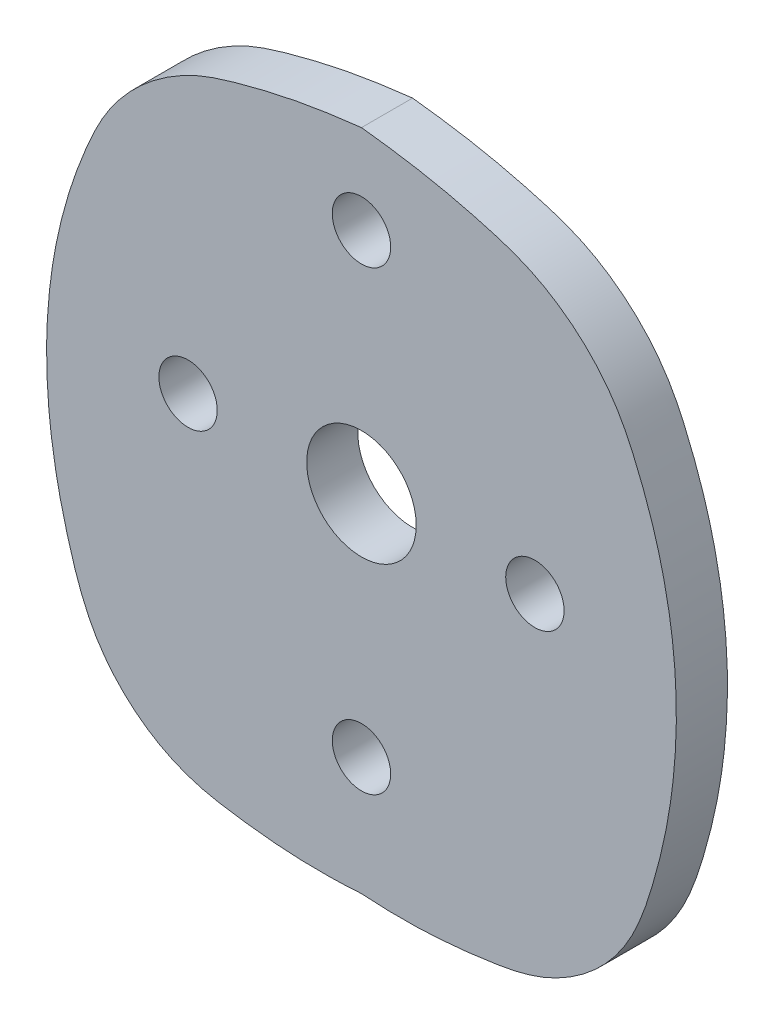
SolidWorks part; units mm, degrees
material "Фанера"
ref_plane "Front Plane" through (0, 0, 0) normal (0, 0, 1) x (1, 0, 0)
ref_plane "Top Plane" through (0, 0, 0) normal (0, 1, 0) x (1, 0, 0)
ref_plane "Right Plane" through (0, 0, 0) normal (1, 0, 0) x (0, 0, -1)
sketch "Эскиз1" plane through (0, 0, 0) normal (0, 0, 1) x (1, 0, 0)
  line L0 (0.0013, 126.9339) -> (0.0013, 78.987) construction
  line L1 (-22.2889, 103.6369) -> (28.0731, 103.6369) construction
  circle A1 centre (0, 103.6369) radius 5.3081 construction
  circle A2 centre (0, 103.6369) radius 3
  circle A3 centre (0.0013, 116.1369) radius 1.6
  circle A4 centre (-9.5, 103.6369) radius 1.6
  circle A5 centre (0.0013, 91.1369) radius 1.6
  circle A6 centre (9.5027, 103.6369) radius 1.6
  spline S2 degree 3 poles (0, 120.2056) (-0.2303, 120.1796) (-0.6919, 120.1276) (-1.3842, 120.0359) (-2.0782, 119.9332) (-2.7732, 119.818) (-3.8045, 119.6287) (-5.1782, 119.3327) (-6.6498, 118.9407) (-7.9278, 118.5587) (-9.0059, 118.1116) (-10.1997, 117.4552) (-11.476, 116.5038) (-12.5105, 115.4161) (-13.2576, 114.3729) (-13.6791, 113.6462) (-13.972, 113.0384) (-14.1742, 112.5846) (-14.5285, 111.758) (-15.0007, 110.522) (-15.6694, 108.3709) (-16.2636, 105.5326) (-16.5285, 102.0693) (-16.3698, 99.17) (-16.0458, 96.8808) (-15.7606, 95.4665) (-15.4698, 94.2939) (-15.237, 93.4525) (-14.9807, 92.621) (-14.7464, 91.9119) (-14.5326, 91.3472) (-14.3505, 90.9304) (-14.1697, 90.5603) (-13.9041, 90.0689) (-13.5269, 89.472) (-12.8147, 88.5541) (-11.7621, 87.5498) (-10.2734, 86.6255) (-9.0119, 86.1602) (-8.0905, 85.9421) (-7.5191, 85.8413) (-6.8456, 85.7341) (-6.0626, 85.6272) (-4.9174, 85.4993) (-3.7596, 85.4154) (-2.6075, 85.3812) (-1.7314, 85.3809) (-0.8583, 85.4054) (-0.2798, 85.4454) (0, 85.4648) knots 0 0 0 0 0.012489 0.025036 0.037639 0.050296 0.063002 0.094154 0.125995 0.145074 0.165995 0.188765 0.218342 0.25144 0.269187 0.287416 0.29663 0.305542 0.314191 0.345101 0.376799 0.435527 0.50097 0.563429 0.591595 0.625539 0.641129 0.656703 0.672584 0.688018 0.696945 0.705118 0.712521 0.71914 0.735218 0.750506 0.781687 0.813037 0.844307 0.853647 0.864055 0.875566 0.890405 0.90664 0.93767 0.952935 0.968753 0.984884 1 1 1 1 construction
  spline S3 degree 3 poles (0, 85.4648) (0.138, 85.4546) (0.4188, 85.4338) (0.8476, 85.4108) (1.291, 85.3937) (1.8867, 85.3806) (2.6195, 85.3814) (3.7793, 85.4163) (4.9467, 85.5018) (6.1015, 85.6319) (6.8903, 85.7408) (7.5665, 85.849) (8.1387, 85.9521) (9.0611, 86.1755) (10.318, 86.6477) (11.8021, 87.581) (12.8482, 88.5906) (13.5563, 89.5144) (14.0022, 90.2291) (14.4009, 91.0159) (14.6777, 91.717) (14.8958, 92.367) (15.0735, 92.9173) (15.2741, 93.5851) (15.4847, 94.3501) (15.7682, 95.5037) (16.053, 96.9233) (16.375, 99.2159) (16.5244, 102.0761) (16.3045, 104.9792) (15.9044, 107.2598) (15.4895, 108.9588) (14.9714, 110.6063) (14.4721, 111.8996) (14.0582, 112.8503) (13.7128, 113.5898) (13.2444, 114.3954) (12.4783, 115.4556) (11.4289, 116.5454) (10.1486, 117.4878) (8.9555, 118.1355) (7.8809, 118.5747) (6.796, 118.8959) (5.7043, 119.1944) (4.5747, 119.4639) (3.4402, 119.6996) (2.2988, 119.9011) (1.1492, 120.0728) (0.3821, 120.1614) (0, 120.2056) knots 0 0 0 0 0.007458 0.015173 0.023144 0.031371 0.047284 0.062633 0.093899 0.110333 0.12526 0.136811 0.14724 0.15658 0.187945 0.219093 0.250433 0.265703 0.281752 0.295757 0.313189 0.322318 0.332706 0.344354 0.359899 0.37546 0.408374 0.437878 0.500184 0.56232 0.594322 0.624895 0.656511 0.687335 0.69956 0.712392 0.731306 0.749676 0.782797 0.812358 0.835004 0.85581 0.874793 0.895944 0.91681 0.937367 0.958388 0.97927 1 1 1 1 construction
  spline S4 degree 1 poles (0.0011, 121.0108) (-0.0019, 84.6628) knots 0 0 1 1 construction
  spline S5 degree 1 poles (-0.0019, 84.6628) (0.0011, 121.0108) knots 0 0 1 1 construction
  spline S6 degree 3 poles (0.0011, 121.0108) (-1.1715, 120.8786) (-2.9203, 120.635) (-5.247, 120.138) (-6.9468, 119.6938) (-8.707, 119.1528) (-10.9465, 118.0205) (-12.8669, 116.3585) (-14.1104, 114.5508) (-14.6798, 113.4284) (-15.1545, 112.3423) (-15.7008, 110.948) (-16.4227, 108.6703) (-17.046, 105.7374) (-17.3264, 102.1531) (-17.1455, 98.5671) (-16.6459, 95.6288) (-16.0391, 93.3198) (-15.5261, 91.6349) (-14.7839, 89.8839) (-13.351, 87.7909) (-11.3097, 86.1718) (-9.2338, 85.3785) (-7.9922, 85.104) (-6.8293, 84.9203) (-5.3528, 84.7301) (-2.9811, 84.5522) (-1.1894, 84.5807) (-0.0019, 84.6628) knots -0.001641 -0.001641 -0.001641 -0.001641 0.060897 0.092166 0.123436 0.154705 0.185974 0.248512 0.279781 0.295416 0.311051 0.34232 0.373589 0.436127 0.498665 0.561204 0.623742 0.655011 0.68628 0.71755 0.748819 0.811357 0.842626 0.858261 0.873895 0.905164 0.936434 0.998972 0.998972 0.998972 0.998972
  spline S7 degree 3 poles (-0.0019, 84.6628) (1.1864, 84.5749) (2.9815, 84.5534) (5.3529, 84.73) (6.8289, 84.92) (7.9925, 85.1043) (9.2339, 85.3783) (11.3098, 86.172) (13.3512, 87.7915) (14.7839, 89.8834) (15.5261, 91.6369) (16.0394, 93.3207) (16.6461, 95.63) (17.1456, 98.5679) (17.3266, 102.1543) (17.0453, 105.7386) (16.4232, 108.6693) (15.7006, 110.9478) (15.1552, 112.3416) (14.6798, 113.4272) (14.1108, 114.551) (12.8669, 116.3578) (10.9469, 118.0206) (8.707, 119.1526) (6.947, 119.694) (5.2465, 120.1381) (2.9206, 120.6356) (1.1727, 120.8754) (0.0011, 121.0108) knots 0.001027 0.001027 0.001027 0.001027 0.063566 0.094835 0.126104 0.141739 0.157373 0.188642 0.251181 0.28245 0.313719 0.344988 0.376257 0.438796 0.501334 0.563872 0.626411 0.65768 0.688949 0.704584 0.720218 0.751487 0.814026 0.845295 0.876564 0.907833 0.939103 1.001641 1.001641 1.001641 1.001641
  dimension "D2" = 6
  dimension "D3" = 3.2
  dimension "D4" = 12.5
  dimension "D5" = 9.5
  dimension "D1" = 0.8
extrude "Бобышка-Вытянуть1" add sketch "Эскиз1" along normal mid plane 2.8
